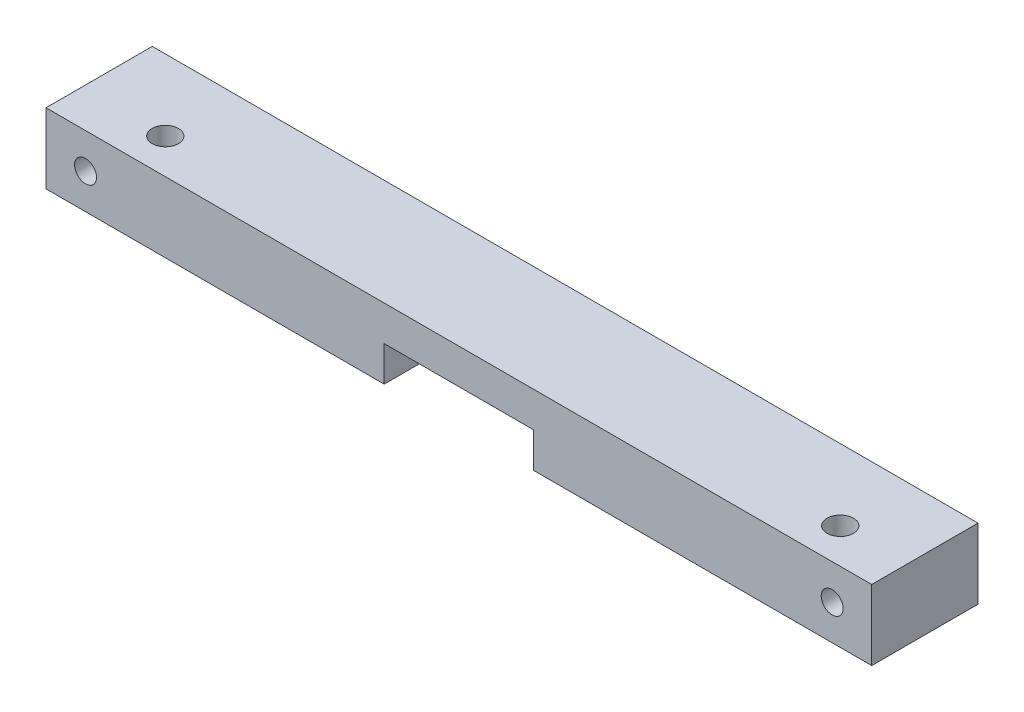
SolidWorks part; units mm, degrees
material "6061-T6 (SS)"
ref_plane "Front" through (0, 0, 0) normal (0, 0, 1) x (1, 0, 0)
ref_plane "Top" through (0, 0, 0) normal (0, 1, 0) x (1, 0, 0)
ref_plane "Right" through (0, 0, 0) normal (1, 0, 0) x (0, 0, -1)
sketch "Sketch1" plane through (0, 0, 0) normal (1, 0, 0) x (0, 0, -1)
  line L1 (0, 0) -> (38.4218, 0)
  line L2 (0, 0) -> (0, 25.4)
  line L3 (0, 25.4) -> (38.4218, 25.4)
  line L4 (38.4218, 0) -> (38.4218, 25.4)
  dimension "D1" = 38.4218
  dimension "D2" = 25.4
extrude "Boss-Extrude1" add sketch "Sketch1" along normal blind 298.45
hole_wizard "3/8-16 Tapped Hole1" positions "Sketch2" profile "Sketch3" tap size "3/8-16" standard "ANSI Inch" end condition through all
sketch "Sketch2" plane through (0, 0, -38.4218) normal (0, 0, -1) x (-1, 0, 0)
  line L0 (-298.45, 0) -> (0, 0) construction
  line L1 (-298.45, 0) -> (-298.45, 25.4) construction
  line L2 (0, 0) -> (0, 25.4) construction
  point P0 (-284.1625, 12.7)
  point P2 (-14.2875, 12.7)
  dimension "D1" = 12.7
  dimension "D2" = 12.7
  dimension "D3" = 14.2875
  dimension "D4" = 14.2875
sketch "Sketch3" plane through (284.1625, 12.7, -38.4218) normal (1, 0, 0) x (0, 1, 0)
  line L0 (0, 0) -> (0, 38.4218)
  line L1 (0, 38.4218) -> (3.9687, 38.4218)
  line L2 (3.9687, 38.4218) -> (3.9687, 0)
  line L5 (3.9687, 0) -> (0, 0)
  line L11 (0, -6.35) -> (0, 107.95) construction
  dimension "Thru Tap Drill Dia." = 7.9375
  dimension "Thru Tap Drill Depth" = 38.4218
hole_wizard "3/8 (0.375) Diameter Hole2" positions "Sketch8" profile "Sketch9" hole size "3/8" standard "ANSI Inch" end condition through all
sketch "Sketch8" plane through (0, 25.4, 0) normal (0, 1, 0) x (1, 0, 0)
  line L0 (298.45, 0) -> (0, 0) construction
  line L1 (0, 38.4218) -> (0, 0) construction
  point P0 (30.4122, 12.7)
  point P2 (274.3878, 12.7)
  dimension "D1" = 12.7
  dimension "D2" = 12.7
  dimension "D3" = 30.4122
  dimension "D4" = 243.9757
sketch "Sketch9" plane through (30.4122, 25.4, -12.7) normal (1, 0, 0) x (0, 0, 1)
  line L0 (0, 0) -> (0, 25.4)
  line L1 (0, 25.4) -> (4.7625, 25.4)
  line L2 (4.7625, 25.4) -> (4.7625, 0)
  line L5 (4.7625, 0) -> (0, 0)
  line L11 (0, -6.35) -> (0, 107.95) construction
  dimension "Thru Hole Dia." = 9.525
  dimension "Thru Hole Depth" = 25.4
sketch "Sketch10" plane through (0, 25.4, 0) normal (0, 1, 0) x (1, 0, 0)
  line L0 (298.45, 38.4218) -> (0, 38.4218) construction
  line L1 (122.2375, 0) -> (176.2125, 0)
  line L2 (122.2375, 0) -> (122.2375, 38.4218)
  line L3 (122.2375, 38.4218) -> (176.2125, 38.4218)
  line L4 (176.2125, 0) -> (176.2125, 38.4218)
  line L5 (298.45, 0) -> (0, 0) construction
  line L6 (0, 38.4218) -> (0, 0) construction
  dimension "D1" = 53.975
  dimension "D2" = 0
  dimension "D3" = 0
  dimension "D4" = 122.2375
sketch "Sketch11" plane through (0, 0, 0) normal (0, -1, 0) x (1, 0, 0)
  line L0 (298.45, 0) -> (0, 0) construction
  line L1 (122.2375, 0) -> (176.2125, 0)
  line L2 (122.2375, 0) -> (122.2375, -38.4218)
  line L3 (122.2375, -38.4218) -> (176.2125, -38.4218)
  line L4 (176.2125, 0) -> (176.2125, -38.4218)
  line L5 (298.45, -38.4218) -> (0, -38.4218) construction
  line L6 (0, 0) -> (0, -38.4218) construction
  dimension "D1" = 53.975
  dimension "D2" = 122.2375
extrude "Cut-Extrude2" cut sketch "Sketch11" against normal blind 12.7
